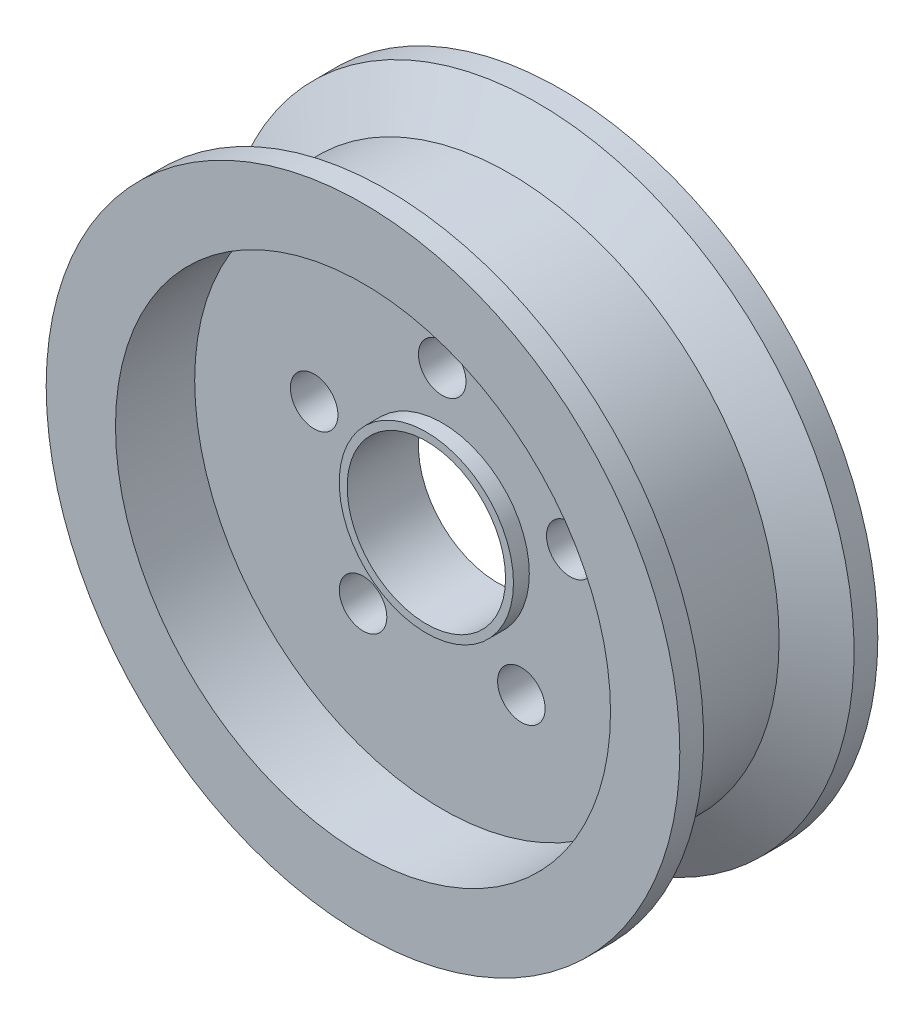
SolidWorks part; units mm, degrees
ref_plane "Front Plane" through (0, 0, 0) normal (0, 0, 1) x (1, 0, 0)
ref_plane "Top Plane" through (0, 0, 0) normal (0, 1, 0) x (1, 0, 0)
ref_plane "Right Plane" through (0, 0, 0) normal (1, 0, 0) x (0, 0, -1)
sketch "Sketch2" plane through (0, 0, 0) normal (0, 0, 1) x (1, 0, 0)
  circle A0 centre (0, 0) radius 40
  circle A1 centre (0, 0) radius 10
  dimension "D1" = 80
  dimension "D2" = 20
extrude "Boss-Extrude1" add sketch "Sketch2" along normal mid plane 25
sketch "Sketch3" plane through (0, 0, 12.5) normal (0, 0, 1) x (1, 0, 0)
  circle A0 centre (0, 0) radius 31.25
  dimension "D1" = 62.5
extrude "Cut-Extrude1" cut sketch "Sketch3" against normal blind 10
sketch "Sketch6" plane through (0, 0, 2.5) normal (0, 0, 1) x (1, 0, 0)
  circle A0 centre (0, 0) radius 11
  circle A1 centre (0, 0) radius 10 construction
  circle A2 centre (0, 0) radius 10
  dimension "D1" = 22
extrude "Boss-Extrude2" add sketch "Sketch6" along normal blind 2
mirror "Mirror1" about plane through (0, 0, 0) normal (0, 0, 1) of "Boss-Extrude2", "Cut-Extrude1"
sketch "Sketch4" plane through (0, 0, 2.5) normal (0, 0, 1) x (1, 0, 0)
  circle A0 centre (0, 17) radius 3
  dimension "D1" = 6
  dimension "D2" = 17
extrude "Cut-Extrude2" cut sketch "Sketch4" against normal through all
pattern_circular "CirPattern1" count 5 over 360 about axis through (0, 0, 0) along (0, 0, 1) of "Cut-Extrude2"
sketch "Sketch5" plane through (0, 0, 0) normal (0, 1, 0) x (1, 0, 0)
  line L0 (0, 19.2675) -> (0, -19.2675) construction
  line L1 (40, 9.5) -> (34, 6.0359)
  line L2 (40, -12.5) -> (40, 12.5) construction
  line L3 (34, 6.0359) -> (34, -6.0359)
  line L4 (34, -6.0359) -> (40, -9.5)
  line L5 (40, -9.5) -> (40, 9.5)
  line L6 (40, 12.5) -> (-40, 12.5) construction
  line L7 (-40, -12.5) -> (40, -12.5) construction
  point P4 (0, 0)
  dimension "D1" = 3
  dimension "D2" = 3
  dimension "D3" = 60
  dimension "D4" = 6
  dimension "D5" = 60
revolve "Cut-Revolve1" cut sketch "Sketch5" angle 360 about L0
